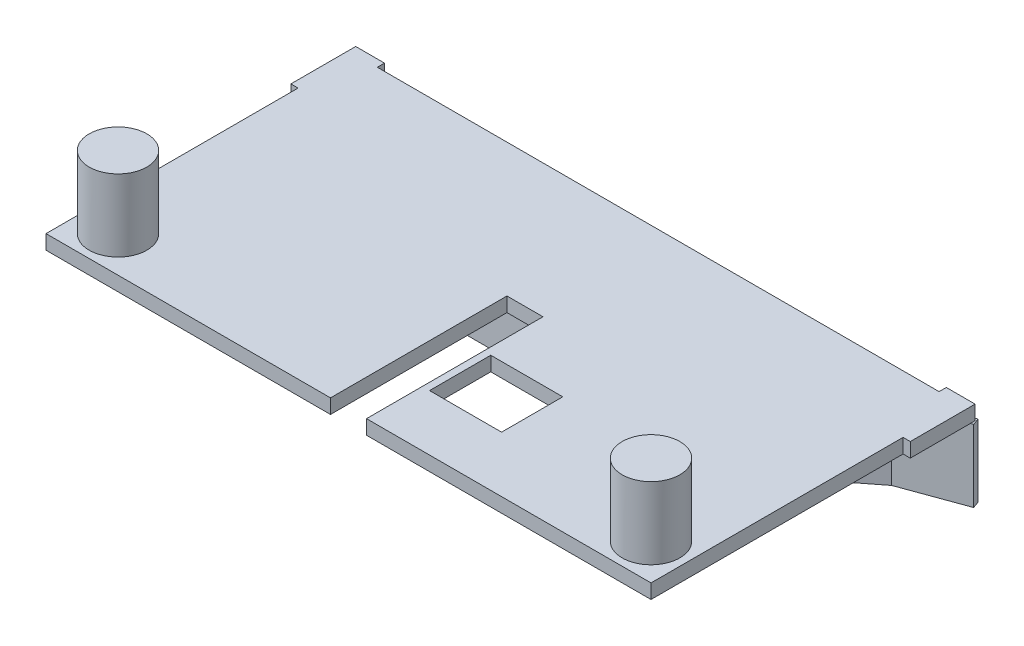
SolidWorks part; units mm, degrees
material "Oak"
ref_plane "Front Plane" through (0, 0, 0) normal (0, 0, 1) x (1, 0, 0)
ref_plane "Top Plane" through (0, 0, 0) normal (0, 1, 0) x (1, 0, 0)
ref_plane "Right Plane" through (0, 0, 0) normal (1, 0, 0) x (0, 0, -1)
sketch "Sketch1" plane through (0, 0, 0) normal (0, 1, 0) x (1, 0, 0)
  line L1 (-273.05, -139.7) -> (273.05, -139.7)
  line L2 (-273.05, -139.7) -> (-273.05, 139.7)
  line L3 (-273.05, 139.7) -> (273.05, 139.7)
  line L4 (273.05, -139.7) -> (273.05, 139.7)
  line L5 (-273.05, -139.7) -> (273.05, 139.7) construction
  line L6 (-273.05, 139.7) -> (273.05, -139.7) construction
  point P0 (0, 0)
  dimension "D1" = 279.4
  dimension "D2" = 546.1
extrude "Boss-Extrude1" add sketch "Sketch1" along normal mid plane 12.7
sketch "Sketch2" plane through (0, 6.35, 0) normal (0, 1, 0) x (1, 0, 0)
  line L0 (-273.05, -139.7) -> (273.05, -139.7) construction
  line L1 (-15.875, 15.875) -> (15.875, 15.875)
  line L2 (-15.875, 15.875) -> (-15.875, -139.7)
  line L3 (-15.875, -139.7) -> (15.875, -139.7)
  line L4 (15.875, 15.875) -> (15.875, -139.7)
  line L5 (-15.875, 15.875) -> (15.875, -139.7) construction
  line L6 (-15.875, -139.7) -> (15.875, 15.875) construction
  line L7 (-266.7, -139.7) -> (-266.7, 82.55)
  line L8 (22.225, -90.4875) -> (85.725, -90.4875)
  line L9 (22.225, -90.4875) -> (22.225, -36.5125)
  line L10 (22.225, -36.5125) -> (85.725, -36.5125)
  line L11 (-266.7, 82.55) -> (-273.05, 82.55)
  line L12 (22.225, -90.4875) -> (85.725, -36.5125) construction
  line L13 (22.225, -36.5125) -> (85.725, -90.4875) construction
  line L14 (-273.05, 82.55) -> (-273.05, -139.7)
  line L15 (-273.05, -139.7) -> (-266.7, -139.7)
  line L16 (85.725, -90.4875) -> (85.725, -36.5125)
  line L17 (273.05, 139.7) -> (-273.05, 139.7) construction
  line L18 (-247.65, 133.35) -> (247.65, 133.35)
  line L19 (-247.65, 133.35) -> (-247.65, 139.7)
  line L20 (-247.65, 139.7) -> (247.65, 139.7)
  line L21 (247.65, 133.35) -> (247.65, 139.7)
  line L22 (-247.65, 133.35) -> (247.65, 139.7) construction
  line L23 (-247.65, 139.7) -> (247.65, 133.35) construction
  line L24 (-273.05, 139.7) -> (-273.05, -139.7) construction
  line L25 (266.7, -139.7) -> (266.7, 82.55)
  line L26 (266.7, 82.55) -> (273.05, 82.55)
  line L27 (273.05, 82.55) -> (273.05, -139.7)
  line L28 (273.05, -139.7) -> (266.7, -139.7)
  point P0 (0, -61.9125)
  point P9 (53.975, -63.5)
  point P18 (0, 136.525)
  dimension "D1" = 31.75
  dimension "D2" = 155.575
  dimension "D3" = 53.975
  dimension "D4" = 6.35
  dimension "D5" = 63.5
  dimension "D6" = 49.2125
  dimension "D7" = 6.35
  dimension "D8" = 222.25
  dimension "D9" = 6.35
  dimension "D10" = 495.3
  dimension "D11" = 6.35
  dimension "D12" = 222.25
extrude "Cut-Extrude1" cut sketch "Sketch2" against normal through all
sketch "Sketch3" plane through (0, -6.35, 0) normal (0, -1, 0) x (1, 0, 0)
  line L0 (222.25, -116.9928) -> (129.1825, -44.45)
  line L1 (-127, -50.8) -> (127, -50.8)
  line L2 (129.1825, -44.45) -> (-129.1825, -44.45)
  line L3 (-129.1825, -44.45) -> (-222.25, -116.9928)
  line L4 (273.05, -139.7) -> (247.65, -139.7) construction
  line L5 (-219.1365, -122.6171) -> (-127, -50.8)
  line L8 (127, -50.8) -> (219.1365, -122.6171)
  line L10 (219.1365, -122.6171) -> (-219.1365, -122.6171) construction
  line L12 (129.1825, -44.45) -> (-129.1825, -44.45) construction
  line L13 (0, -42.3393) -> (0, -133.35) construction
  line L14 (-247.65, -133.35) -> (247.65, -133.35) construction
  line L15 (273.05, -82.55) -> (273.05, -139.7) construction
  line L16 (0, -133.35) -> (0, -122.6171) construction
  line L17 (222.25, -116.9928) -> (275.2218, -136.273)
  line L18 (275.2218, -136.273) -> (273.05, -142.24)
  line L19 (0, -142.24) -> (0, -42.3393) construction
  line L20 (273.05, -142.24) -> (219.1365, -122.6171)
  line L21 (-222.25, -116.9928) -> (-275.2218, -136.273)
  line L22 (-275.2218, -136.273) -> (-273.05, -142.24)
  line L23 (-273.05, -142.24) -> (-219.1365, -122.6171)
  line L24 (273.05, -142.24) -> (-273.05, -142.24) construction
  dimension "D2" = 6.35
  dimension "D3" = 6.35
  dimension "D4" = 546.1
  dimension "D5" = 444.5
  dimension "D6" = 254
  dimension "D7" = 82.55
  dimension "D8" = 6.35
  dimension "D9" = 6.35
  dimension "D10" = 160
  dimension "D11" = 6.35
  dimension "D12" = 2.54
extrude "Extrude2" add sketch "Sketch3" along normal blind 63.5
sketch "Sketch4" plane through (0, 6.35, 0) normal (0, 1, 0) x (1, 0, 0)
  line L0 (266.7, 82.55) -> (266.7, -139.7) construction
  line L2 (-247.65, 133.35) -> (247.65, 133.35) construction
  line L3 (-266.7, -139.7) -> (-266.7, 82.55) construction
  circle A0 centre (234.95, -107.95) radius 25.4
  circle A1 centre (-234.95, -107.95) radius 25.4
  dimension "D1" = 50.8
  dimension "D2" = 31.75
  dimension "D4" = 50.8
  dimension "D3" = 241.3
  dimension "D5" = 31.75
  dimension "D6" = 241.3
extrude "Boss-Extrude2" add sketch "Sketch4" along normal blind 63.5
